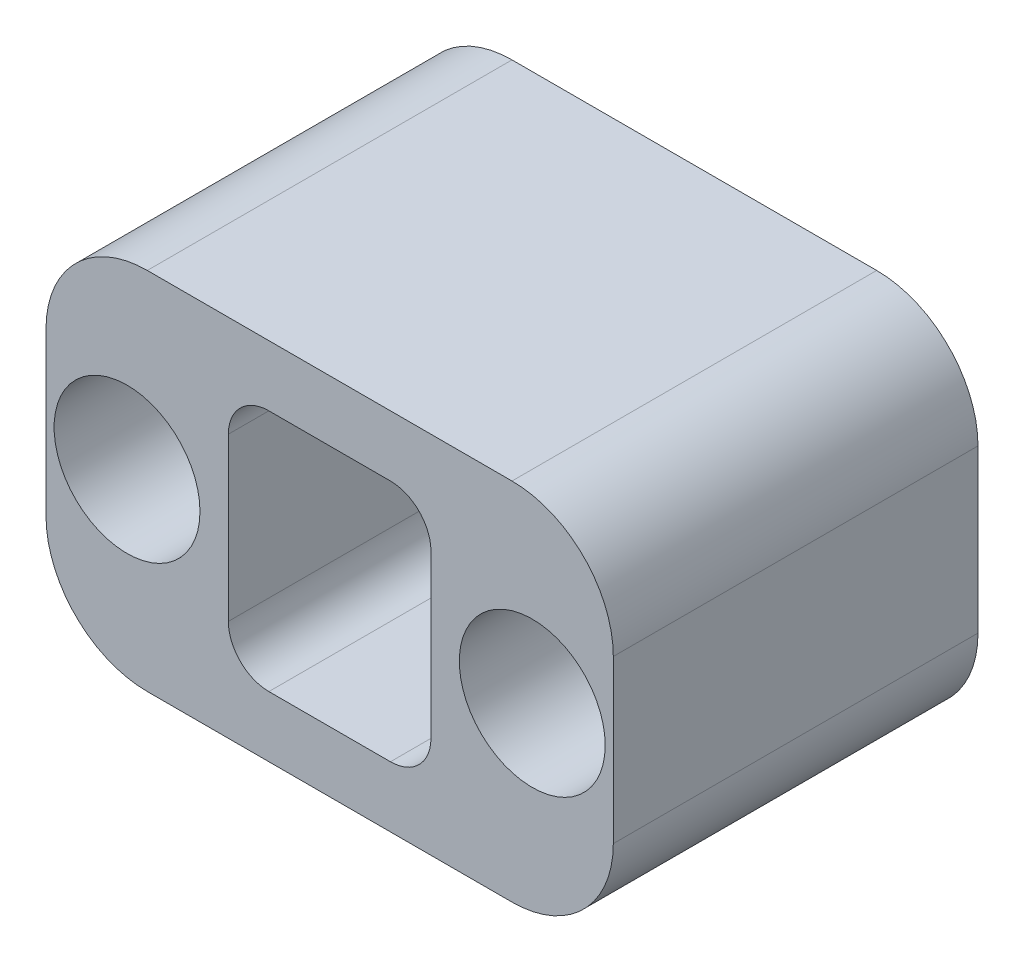
SolidWorks part; units mm, degrees
material "环氧树脂,未充填"
ref_plane "前视基准面" through (0, 0, 0) normal (0, 0, 1) x (1, 0, 0)
ref_plane "上视基准面" through (0, 0, 0) normal (0, 1, 0) x (1, 0, 0)
ref_plane "右视基准面" through (0, 0, 0) normal (1, 0, 0) x (0, 0, -1)
other "Configuration Table"
sketch "草图1" plane through (0, 0, 0) normal (0, 0, 1) x (1, 0, 0)
  line L0 (-10, 0) -> (10, 0) construction
  line L2 (-14, -9) -> (14, -9)
  line L3 (-14, -9) -> (-14, 9)
  line L4 (-14, 9) -> (14, 9)
  line L5 (14, -9) -> (14, 9)
  line L6 (-14, -9) -> (14, 9) construction
  line L7 (-14, 9) -> (14, -9) construction
  circle A0 centre (-10, 0) radius 2.1
  circle A1 centre (10, 0) radius 2.1
  point P4 (0, 0)
  point P7 (0, 0)
  dimension "D1" = 4.2
  dimension "D2" = 20
  dimension "D3" = 18
  dimension "D4" = 4
extrude "凸台-拉伸1" add sketch "草图1" along normal blind 18
sketch "草图2" plane through (0, 0, 18) normal (0, 0, 1) x (1, 0, 0)
  circle A0 centre (-10, 0) radius 3.6
  circle A1 centre (10, 0) radius 3.6
  dimension "D1" = 7.2
extrude "切除-拉伸1" cut sketch "草图2" against normal blind 15
sketch "草图3" plane through (0, 0, 18) normal (0, 0, 1) x (1, 0, 0)
  line L0 (14, 9) -> (-14, 9) construction
  line L1 (-5, -6) -> (5, -6)
  line L2 (-5, -6) -> (-5, 6)
  line L3 (-5, 6) -> (5, 6)
  line L4 (5, -6) -> (5, 6)
  line L5 (-5, -6) -> (5, 6) construction
  line L6 (-5, 6) -> (5, -6) construction
  point P0 (0, 0)
  dimension "D1" = 10
  dimension "D2" = 3
extrude "切除-拉伸2" cut sketch "草图3" against normal blind 25
fillet "圆角1" radius 2 4 edges at (5, -6, 9) (-5, 6, 9) (5, 6, 9) (-5, -6, 9)
fillet "圆角2" radius 5 4 edges at (14, -9, 9) (-14, -9, 9) (-14, 9, 9) (14, 9, 9)
